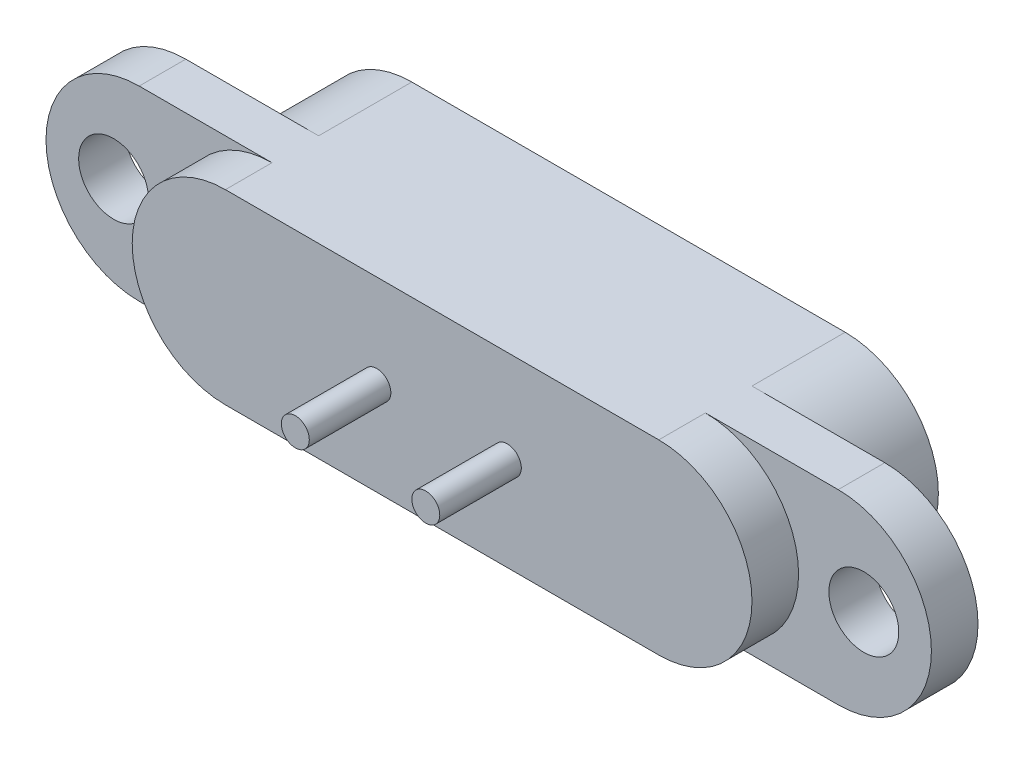
SolidWorks part; units mm, degrees
ref_plane "前视基准面" through (0, 0, 0) normal (0, 0, 1) x (1, 0, 0)
ref_plane "上视基准面" through (0, 0, 0) normal (0, 1, 0) x (1, 0, 0)
ref_plane "右视基准面" through (0, 0, 0) normal (1, 0, 0) x (0, 0, -1)
sketch "草图1" plane through (0, 0, 0) normal (0, 0, 1) x (1, 0, 0)
  line L0 (0, 0) -> (9.3, 0) construction
  line L1 (0, 2) -> (9.3, 2)
  line L2 (0, -2) -> (9.3, -2)
  arc A0 (0, 2) -> (0, -2) centre (0, 0) ccw
  arc A1 (9.3, -2) -> (9.3, 2) centre (9.3, 0) ccw
  point P3 (4.65, 0)
  dimension "D1" = 9.3
  dimension "D2" = 4
extrude "凸台-拉伸1" add sketch "草图1" along normal blind 4
sketch "草图2" plane through (0, 0, 0) normal (0, 0, -1) x (-1, 0, 0)
  line L0 (-12.15, 0) -> (2.85, 0) construction
  line L1 (-12.15, 2) -> (2.85, 2)
  line L2 (-12.15, -2) -> (2.85, -2)
  line L3 (-9.3, 2) -> (0, 2) construction
  line L4 (-12.7, 0) -> (3.4, 0) construction
  arc A0 (-12.15, 2) -> (-12.15, -2) centre (-12.15, 0) ccw
  arc A1 (2.85, -2) -> (2.85, 2) centre (2.85, 0) ccw
  circle A2 centre (-12.7, 0) radius 0.75
  circle A3 centre (3.4, 0) radius 0.75
  point P2 (-4.65, 0)
  point P7 (-14.15, 0)
  point P8 (4.85, 0)
  point P11 (-4.65, 2)
  point P15 (-4.65, 2)
  point P18 (-4.65, 0)
  point P19 (-12.7, -0.8158)
  dimension "D3" = 1.5
  dimension "D4" = 1.5
  dimension "D1" = 4
  dimension "D2" = 19
  dimension "D5" = 16.1
extrude "凸台-拉伸2" add sketch "草图2" against normal blind 1 from offset 2 offset against normal yes
sketch "草图3" plane through (0, 0, 0) normal (0, 0, -1) x (-1, 0, 0)
  line L0 (-6.05, 0) -> (-3.25, 0) construction
  line L1 (-9.3, 2) -> (0, 2) construction
  circle A0 centre (-6.05, 0) radius 0.75
  circle A1 centre (-3.25, 0) radius 0.75
  point P6 (-4.65, 2)
  point P7 (-4.65, 0)
  dimension "D1" = 1.5
  dimension "D2" = 1.5
  dimension "D3" = 2.8
extrude "切除-拉伸1" cut sketch "草图3" against normal blind 0.1
sketch "草图4" plane through (0, 0, 4) normal (0, 0, 1) x (1, 0, 0)
  circle A0 centre (3.25, 0) radius 0.3
  circle A1 centre (3.25, 0) radius 0.75
  circle A2 centre (3.25, 0) radius 0.75 construction
  circle A3 centre (6.05, 0) radius 0.75
  circle A4 centre (6.05, 0) radius 0.75 construction
  circle A5 centre (6.05, 0) radius 0.3
  dimension "D3" = 0.6
  dimension "D4" = 0.6
  dimension "D1" = 0
  dimension "D2" = 0
extrude "凸台-拉伸3" add sketch "草图4" along normal blind 1.75
